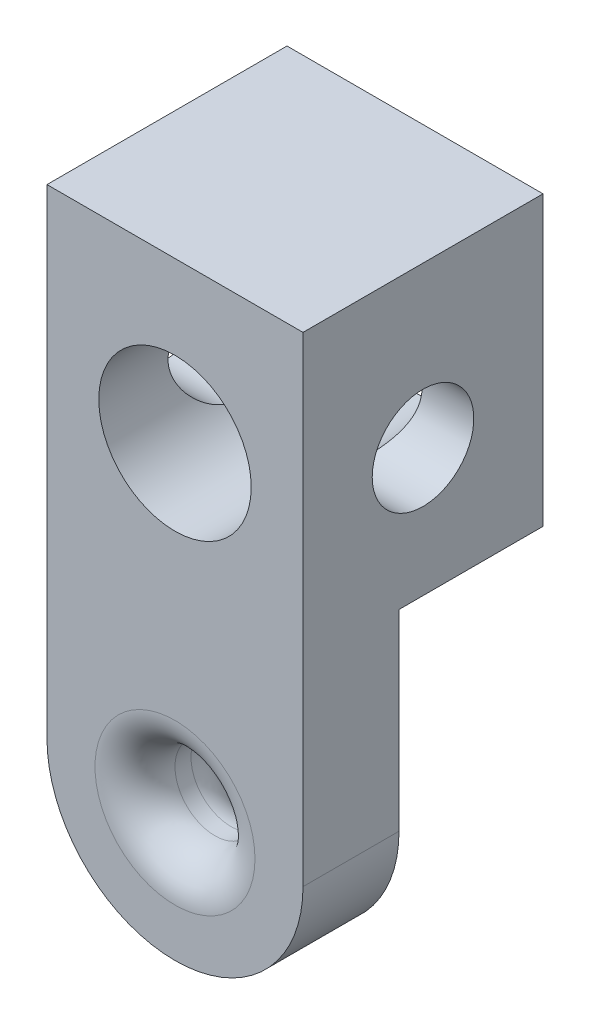
SolidWorks part; units mm, degrees
material "Delrin 2700 NC010, Low Viscosity Acetal Copolymer (SS)"
ref_plane "Front" through (0, 0, 0) normal (0, 0, 1) x (1, 0, 0)
ref_plane "Top" through (0, 0, 0) normal (0, 1, 0) x (1, 0, 0)
ref_plane "Right" through (0, 0, 0) normal (1, 0, 0) x (0, 0, -1)
sketch "Sketch1" plane through (0, 0, 0) normal (0, 0, 1) x (1, 0, 0)
  line L0 (0, 20) -> (0, 0) construction
  line L1 (-8, 12) -> (-8, 0)
  line L2 (8, 12) -> (8, 0)
  line L5 (8, 12) -> (8, 30)
  line L6 (8, 30) -> (-8, 30)
  line L7 (-8, 30) -> (-8, 12)
  arc A0 (-8, 0) -> (8, 0) centre (0, 0) ccw
  circle A2 centre (0, 0) radius 2.5
  circle A3 centre (0, 20) radius 2.6 construction
  dimension "D1" = 16
  dimension "D2" = 16
  dimension "D4" = 5.2
  dimension "D5" = 5
  dimension "D3" = 20
  dimension "D6" = 10
  dimension "D7" = 18
extrude "Boss-Extrude1" add sketch "Sketch1" along normal blind 15
sketch "Sketch6" plane through (0, 0, 0) normal (0, 0, 1) x (1, 0, 0)
  line L0 (8, 0) -> (8, 30) construction
  line L1 (8, 12) -> (-8, 12)
  line L2 (8, 12) -> (8, -8)
  line L3 (8, -8) -> (-8, -8)
  line L4 (-8, 12) -> (-8, -8)
  line L5 (-8, 30) -> (-8, 0) construction
  arc A0 (-8, 0) -> (8, 0) centre (0, 0) ccw construction
  dimension "D1" = 20
extrude "Cut-Extrude1" cut sketch "Sketch6" along normal blind 9
fillet "Fillet1" radius 2.5 2 edges at (2.5, 0, 15) (-2.5, 0, 9)
hole_wizard "3/8 (0.3750) Dowel Hole1" positions "Sketch2" profile "Sketch3" hole size "3/8" standard "ANSI Inch" end condition through all
sketch "Sketch2" plane through (0, 0, 15) normal (0, 0, 1) x (1, 0, 0)
  point P0 (0, 20)
sketch "Sketch3" plane through (0, 20, 15) normal (1, 0, 0) x (0, -1, 0)
  line L0 (0, 0) -> (0, 15)
  line L1 (0, 15) -> (4.7625, 15)
  line L2 (4.7625, 15) -> (4.7625, 0)
  line L5 (4.7625, 0) -> (0, 0)
  line L11 (0, -6.35) -> (0, 107.95) construction
  dimension "Thru Hole Dia." = 9.525
  dimension "Thru Hole Depth" = 15
hole_wizard "1/4 (0.2500) Dowel Hole2" positions "Sketch4" profile "Sketch5" hole size "1/4" standard "ANSI Inch" end condition through all
sketch "Sketch4" plane through (-8, 0, 0) normal (-1, 0, 0) x (0, 0, 1)
  line L0 (7.5, 30) -> (7.5, 20) construction
  line L1 (15, 30) -> (0, 30) construction
  point P0 (7.5, 20)
sketch "Sketch5" plane through (-8, 20, 7.5) normal (0, 1, 0) x (0, 0, 1)
  line L0 (0, 0) -> (0, 16)
  line L1 (0, 16) -> (3.175, 16)
  line L2 (3.175, 16) -> (3.175, 0)
  line L5 (3.175, 0) -> (0, 0)
  line L11 (0, -6.35) -> (0, 107.95) construction
  dimension "Thru Hole Dia." = 6.35
  dimension "Thru Hole Depth" = 16
